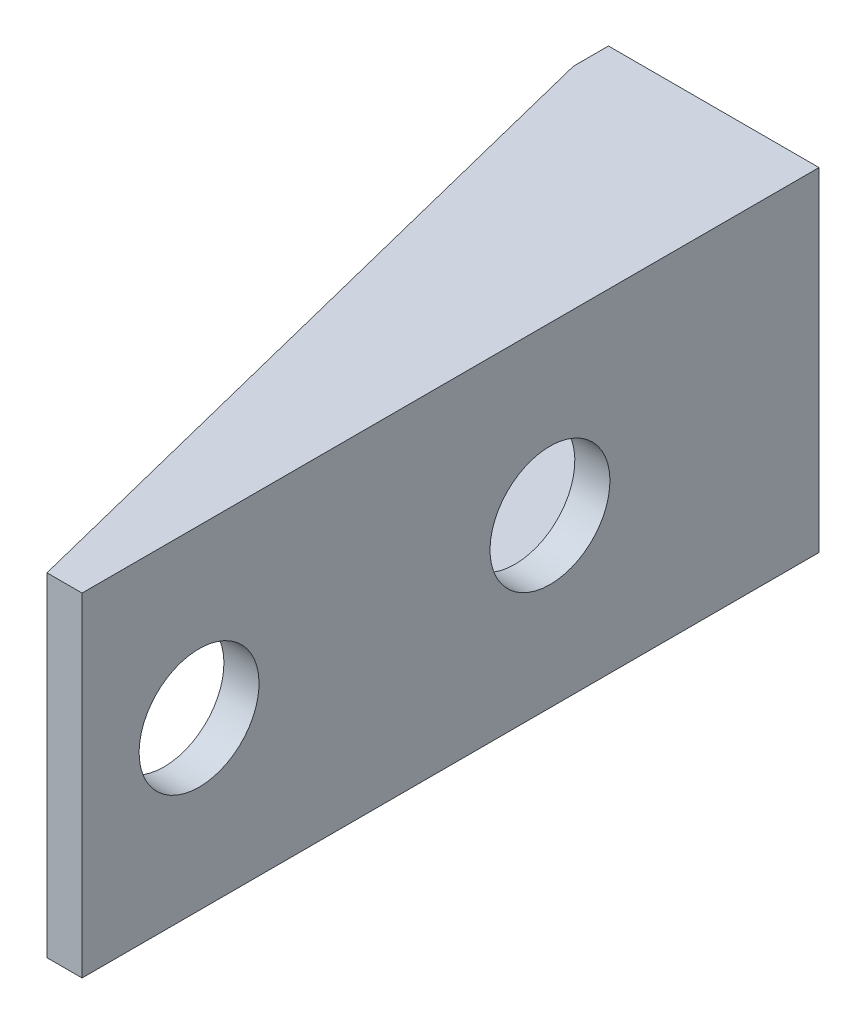
SolidWorks part; units mm, degrees
material "사용자정의 플라스틱"
ref_plane "정면" through (0, 0, 0) normal (0, 0, 1) x (1, 0, 0)
ref_plane "윗면" through (0, 0, 0) normal (0, 1, 0) x (1, 0, 0)
ref_plane "우측면" through (0, 0, 0) normal (1, 0, 0) x (0, 0, -1)
sketch "스케치1" plane through (0, 0, 0) normal (0, 0, 1) x (1, 0, 0)
  line L1 (-3.6, 2.5) -> (3.6, 2.5)
  line L2 (-3.6, 2.5) -> (-3.6, -2.5)
  line L3 (-3.6, -2.5) -> (3.6, -2.5)
  line L4 (3.6, 2.5) -> (3.6, -2.5)
  line L5 (-3.6, 2.5) -> (3.6, -2.5) construction
  line L6 (-3.6, -2.5) -> (3.6, 2.5) construction
  point P0 (0, 0)
  dimension "D1" = 5
  dimension "D2" = 7.2
extrude "보스-돌출1" add sketch "스케치1" along normal blind 1.2 contours L2 L3 L4 L1
sketch "스케치2" plane through (0, 0, 1.2) normal (0, 0, 1) x (1, 0, 0)
  line L1 (-2.6, 0) -> (-2.6, 3.1914) construction
  line L2 (-3.6, 2.5) -> (-3.6, -2.5) construction
  line L3 (-3.6, -2.5) -> (3.6, -2.5) construction
  circle A0 centre (-0.75, 0) radius 1.85
  dimension "D1" = 3.7
  dimension "D2" = 1
  dimension "D3" = 2.5
extrude "컷-돌출1" cut sketch "스케치2" against normal through all
sketch "스케치3" plane through (0, 0, 1.2) normal (0, 0, 1) x (1, 0, 0)
  line L0 (-3.6, -2.5) -> (3.6, -2.5) construction
  line L1 (3.6, 2.5) -> (2.4, 2.5)
  line L2 (3.6, 2.5) -> (3.6, -2.5)
  line L3 (3.6, -2.5) -> (2.4, -2.5)
  line L4 (2.4, 2.5) -> (2.4, -2.5)
  dimension "D1" = 1.2
extrude "보스-돌출2" add sketch "스케치3" along normal blind 24
fillet "필렛1" radius 0.3 1 edges at (2.4, 0, 1.2)
sketch "스케치4" plane through (2.4, 0, 0) normal (-1, 0, 0) x (0, 0, 1)
  line L3 (25.2, -2.5) -> (1.5, -2.5) construction
  line L4 (25.2, 2.5) -> (25.2, -2.5) construction
  circle A0 centre (21.2, 0) radius 2.05
  circle A1 centre (9.2, 0) radius 2.05
  dimension "D1" = 4.1
  dimension "D4" = 4.1
  dimension "D2" = 2.5
  dimension "D3" = 4
  dimension "D6" = 12
extrude "컷-돌출2" cut sketch "스케치4" against normal through all
sketch "스케치6" plane through (0, -2.5, 0) normal (0, -1, 0) x (1, 0, 0)
  line L0 (-3.6, 1.2) -> (-3.6, 0)
  line L1 (-3.6, 0) -> (3.6, 0)
  line L2 (3.6, 0) -> (3.6, 25.2)
  line L3 (2.4, 25.2) -> (3.6, 25.2) construction
  line L4 (3.6, 25.2) -> (3.6, 0) construction
  line L5 (3.6, 25.2) -> (2.4, 25.2)
  line L6 (2.4, 25.2) -> (2.4, 1.5)
  line L7 (2.1, 1.2) -> (-3.6, 1.2)
  arc A0 (2.4, 1.5) -> (2.1, 1.2) centre (2.1, 1.5) cw
  dimension "D1" = 0.3
extrude "보스-돌출4" add sketch "스케치6" along normal blind 2
ref_plane "평면1" through (0, 0, 0) normal (0, 1, 0) x (1, 0, 0)
mirror "대칭 복사1" about plane through (0, 0, 0) normal (0, 1, 0) of "보스-돌출4"
sketch "스케치7" plane through (0, -4.5, 0) normal (0, -1, 0) x (-1, 0, 0)
  line L0 (3.6, 0) -> (-3.6, 0)
  line L1 (-3.6, 0) -> (-3.6, -25.2)
  line L2 (-3.6, -25.2) -> (-2.4, -25.2)
  line L3 (-2.4, -25.2) -> (3.6, -1.2)
  line L4 (-2.1, -1.2) -> (3.6, -1.2) construction
  line L5 (3.6, -1.2) -> (3.6, 0)
extrude "보스-돌출5" add sketch "스케치7" along normal blind 1.2
mirror "대칭 복사2" about plane through (0, 0, 0) normal (0, 1, 0) of "보스-돌출5"
